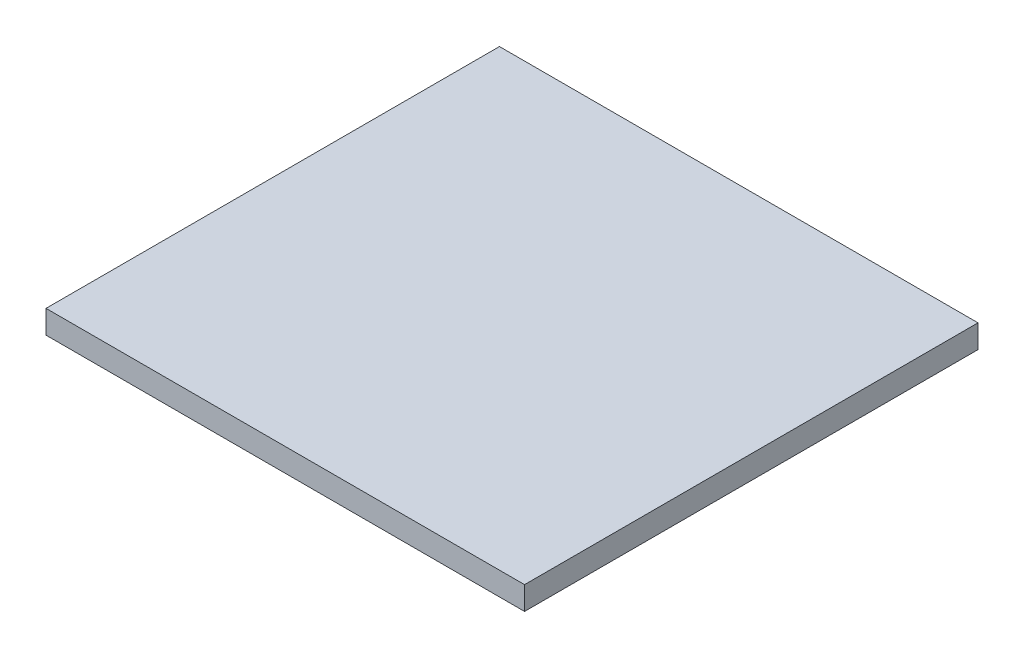
SolidWorks part; units mm, degrees
ref_plane "Front Plane" through (0, 0, 0) normal (0, 0, 1) x (1, 0, 0)
ref_plane "Top Plane" through (0, 0, 0) normal (0, 1, 0) x (1, 0, 0)
ref_plane "Right Plane" through (0, 0, 0) normal (1, 0, 0) x (0, 0, -1)
sketch "Sketch1" plane through (0, 0, 0) normal (0, 1, 0) x (1, 0, 0)
  line L1 (-65.9453, 79.2259) -> (64.8647, 79.2259)
  line L2 (-65.9453, 79.2259) -> (-65.9453, -44.7261)
  line L3 (-65.9453, -44.7261) -> (64.8647, -44.7261)
  line L4 (64.8647, 79.2259) -> (64.8647, -44.7261)
  dimension "D1" = 130.81
  dimension "D2" = 123.952
extrude "Boss-Extrude1" add sketch "Sketch1" along normal blind 6.35
